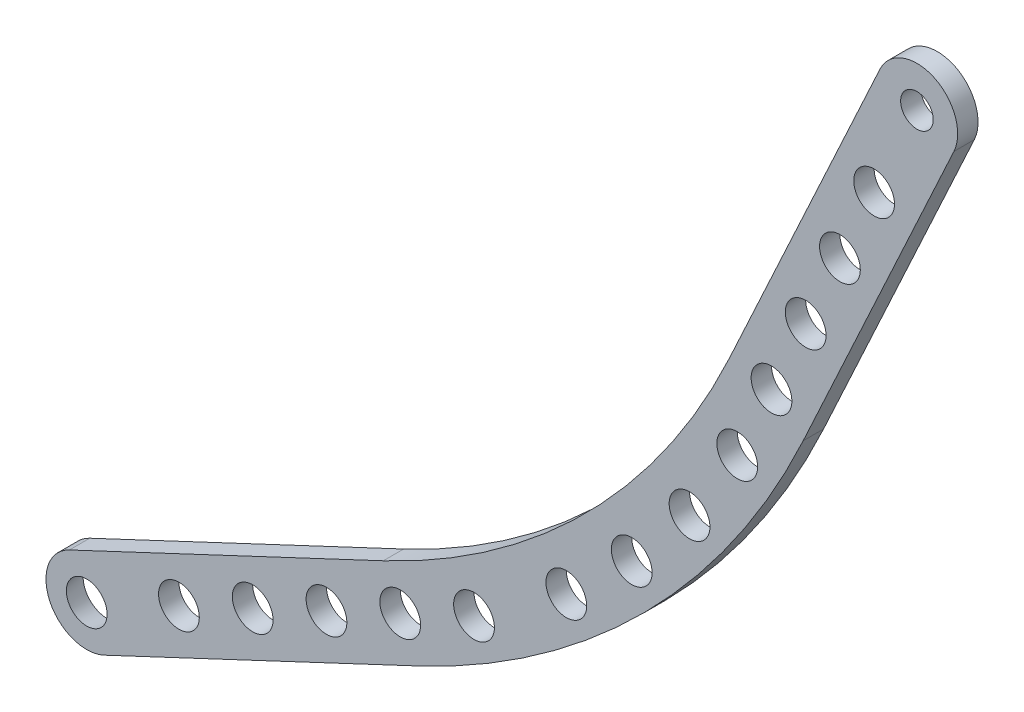
SolidWorks part; units mm, degrees
material "Acier allié"
ref_plane "Face" through (0, 0, 0) normal (0, 0, 1) x (1, 0, 0)
ref_plane "Dessus" through (0, 0, 0) normal (0, 1, 0) x (1, 0, 0)
ref_plane "Droite" through (0, 0, 0) normal (1, 0, 0) x (0, 0, -1)
sketch "Esquisse1" plane through (0, 0, 0) normal (0, 0, 1) x (1, 0, 0)
  line L0 (84.1056, 87.1404) -> (47.1251, 7.1759) construction
  line L1 (-119.5789, -119.2878) -> (-42.5562, -83.0745) construction
  line L2 (75.0292, 91.3379) -> (38.0487, 11.3734)
  line L3 (93.182, 82.9429) -> (56.2015, 2.9784)
  line L4 (-123.8338, -110.2382) -> (-46.811, -74.0248)
  line L5 (-115.3241, -128.3375) -> (-38.3014, -92.1242)
  arc A0 (-123.8338, -110.2382) -> (-115.3241, -128.3375) centre (-119.5789, -119.2878) ccw
  arc A1 (93.182, 82.9429) -> (75.0292, 91.3379) centre (84.1056, 87.1404) ccw
  arc A2 (-38.3014, -92.1242) -> (56.2015, 2.9784) centre (-121.696, 85.2493) ccw
  arc A3 (-46.811, -74.0248) -> (38.0487, 11.3734) centre (-121.696, 85.2493) ccw
  circle A4 centre (84.1056, 87.1404) radius 4
  point P16 (18.7087, -54.27)
  dimension "D4" = 20
  dimension "D5" = 196
  dimension "D6" = 176
  dimension "D7" = 8
  dimension "D1" = 290
  dimension "D2" = 155.8
  dimension "D3" = 140
extrude "Base-Extrusion" add sketch "Esquisse1" along normal blind 5
ref_plane "Plan1" through (24.2835, -51.6489, 0) normal (0.4255, -0.905, 0) x (0.905, 0.4255, 0)
sketch "Esquisse3" plane through (24.2835, -51.6489, 0) normal (0.4255, -0.905, 0) x (0.905, 0.4255, 0)
  line L0 (-158.9699, 13.4245) -> (-158.9699, -9.4834) construction
  line L1 (-158.9699, 5) -> (-158.9699, 0) construction
  line L2 (-158.9699, 5) -> (-153.9699, 5)
  line L4 (-158.9699, 5) -> (-73.8587, 5) construction
  line L6 (-153.9699, 5) -> (-153.0882, 0)
  line L7 (-158.9699, 0) -> (-158.9699, 5)
  line L8 (-158.9699, 0) -> (-73.8587, 0) construction
  line L9 (-153.0882, 0) -> (-158.9699, 0)
  dimension "D1" = 5
  dimension "D2" = 10
revolve "Enlèvement de matière-Révolution2" cut sketch "Esquisse3" angle 360 about L0
sketch "Esquisse4" plane through (0, 0, 5) normal (0, 0, 1) x (1, 0, 0)
  line L0 (84.1056, 87.1404) -> (47.1251, 7.1759) construction
  line L1 (73.6119, 64.4494) -> (65.2169, 46.2966) construction
  circle A0 centre (73.6119, 64.4494) radius 5
  circle A1 centre (65.2169, 46.2966) radius 5
  circle A2 centre (56.8219, 28.1438) radius 5
  circle A3 centre (48.4269, 9.991) radius 5
  circle A4 centre (40.0319, -8.1618) radius 5
  dimension "D1" = 10
  dimension "D2" = 25
  dimension "D3" = 20
extrude "Enlèv. mat.-Extru.1" cut sketch "Esquisse4" against normal through all
sketch "Esquisse5" plane through (0, 0, 5) normal (0, 0, 1) x (1, 0, 0)
  line L0 (-119.5789, -119.2878) -> (-42.5562, -83.0745) construction
  circle A0 centre (-96.9548, -108.6508) radius 5
  circle A1 centre (-78.8554, -100.1411) radius 5
  circle A2 centre (-60.7561, -91.6314) radius 5
  circle A3 centre (-42.6568, -83.1218) radius 5
  circle A4 centre (-24.5575, -74.6121) radius 5
  dimension "D2" = 10
  dimension "D1" = 25
extrude "Enlèv. mat.-Extru.2" cut sketch "Esquisse5" against normal blind 5
sketch "Esquisse11" plane through (0, 0, 5) normal (0, 0, 1) x (1, 0, 0)
  line L0 (-35.7485, -70.3312) -> (-94.9919, 55.6746) construction
  line L1 (33.6683, -3.8258) -> (-94.9919, 55.6746) construction
  line L2 (-123.8338, -110.2382) -> (-46.811, -74.0248) construction
  line L3 (75.0292, 91.3379) -> (38.0487, 11.3734) construction
  circle A0 centre (-121.696, 85.2493) radius 187.2339
sketch "Esquisse12" plane through (0, 0, 5) normal (0, 0, 1) x (1, 0, 0)
  circle A0 centre (-1.9093, -58.6523) radius 5
  circle A1 centre (14.1431, -43.6083) radius 5
  circle A2 centre (28.32, -26.7852) radius 5
  circle A3 centre (40.0319, -8.1618) radius 5 construction
  circle A6 centre (-121.696, 85.2493) radius 187.2339 construction
  dimension "D1" = 10
  dimension "D2" = 22
  dimension "D3" = 22
  dimension "D4" = 22
extrude "Enlèv. mat.-Extru.3" cut sketch "Esquisse12" against normal through all
sketch "Esquisse13" plane through (0, 0, 5) normal (0, 0, 1) x (1, 0, 0)
  line L0 (84.1056, 87.1404) -> (-119.5789, -119.2878) construction
ref_plane "Plan2" through (84.1056, 87.1404, 5) normal (-0.7024, -0.7118, 0) x (0.7118, -0.7024, 0)
ref_plane "Plan3" through (-119.5789, -119.2878, 5) normal (-0.7024, -0.7118, 0) x (0.7118, -0.7024, 0)
